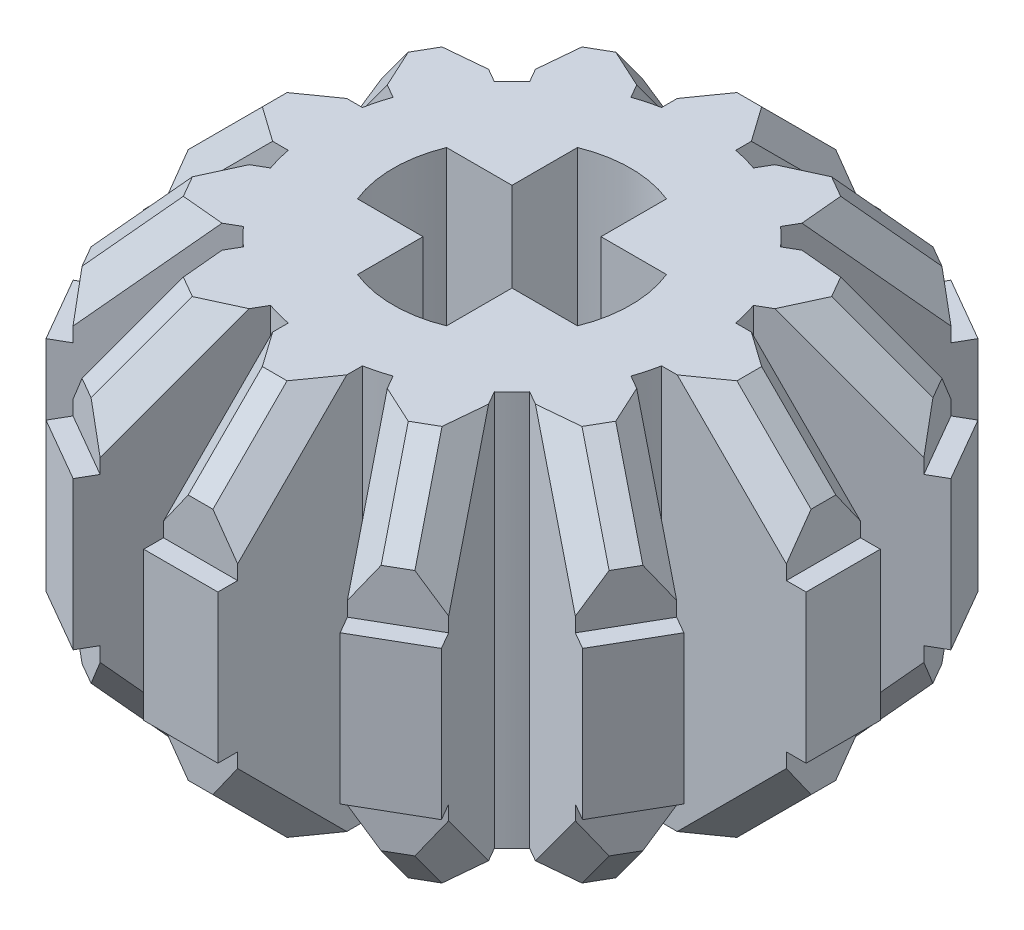
SolidWorks part; units mm, degrees
ref_plane "Front Plane" through (0, 0, 0) normal (0, 0, 1) x (1, 0, 0)
ref_plane "Top Plane" through (0, 0, 0) normal (0, 1, 0) x (1, 0, 0)
ref_plane "Right Plane" through (0, 0, 0) normal (1, 0, 0) x (0, 0, -1)
sketch "Sketch1" plane through (0, 0, 0) normal (0, 1, 0) x (1, 0, 0)
  circle A0 centre (0, 0) radius 3.85
  dimension "D1" = 7.7
extrude "Gear Body" add sketch "Sketch1" along normal mid plane 8
sketch "Sketch2" plane through (0, 0, 0) normal (0, 1, 0) x (1, 0, 0)
  line L1 (0.75, -6.7) -> (-0.75, -6.7)
  line L2 (0.75, -6.7) -> (0.75, 6.7)
  line L3 (0.75, 6.7) -> (-0.75, 6.7)
  line L4 (-0.75, -6.7) -> (-0.75, 6.7)
  line L5 (0.75, -6.7) -> (-0.75, 6.7) construction
  line L6 (0.75, 6.7) -> (-0.75, -6.7) construction
  circle A0 centre (0, 0) radius 3.85 construction
  circle A1 centre (0, 0) radius 3.85
  point P0 (0, 0)
  dimension "D1" = 1.5
  dimension "D2" = 13.4
extrude "Tooth Middle " add sketch "Sketch2" along normal mid plane 3 contours A1 L2 L3 L4
sketch "Sketch3" plane through (0, 0, 0) normal (0, 1, 0) x (1, 0, 0)
  line L0 (-0.75, 3.7762) -> (-0.75, 6.7) construction
  line L1 (0.75, -6.3) -> (-0.75, -6.3)
  line L2 (0.75, -6.3) -> (0.75, 6.3)
  line L3 (0.75, 6.3) -> (-0.75, 6.3)
  line L4 (-0.75, -6.3) -> (-0.75, 6.3)
  line L5 (0.75, -6.3) -> (-0.75, 6.3) construction
  line L6 (0.75, 6.3) -> (-0.75, -6.3) construction
  circle A0 centre (0, 0) radius 3.85 construction
  circle A1 centre (0, 0) radius 3.85
  point P0 (0, 0)
  dimension "D1" = 12.6
extrude "Tooth Outer" add sketch "Sketch3" along normal mid plane 8 contours A1 L2 L3 L4
chamfer "Chamfer1" distance 1.5 angle 45 2 edges at (0, -4, -6.3) (0, 4, -6.3)
chamfer "Chamfer2" distance 0.5 angle 45 4 edges at (0.75, -3.25, -5.55) (-0.75, -3.25, -5.55) (0.75, 3.25, -5.55) (-0.75, 3.25, -5.55)
pattern_circular "CirPattern1" count 12 over 360 about axis through (0, 0, 0) along (0, 1, 0) of "Tooth Middle ", "Tooth Outer", "Chamfer1", "Chamfer2"
sketch "Sketch4" plane through (0, 0, 0) normal (0, 1, 0) x (1, 0, 0)
  line L1 (2.4, -0.9) -> (-2.4, -0.9)
  line L2 (2.4, -0.9) -> (2.4, 0.9)
  line L3 (2.4, 0.9) -> (-2.4, 0.9)
  line L4 (-2.4, -0.9) -> (-2.4, 0.9)
  line L5 (2.4, -0.9) -> (-2.4, 0.9) construction
  line L6 (2.4, 0.9) -> (-2.4, -0.9) construction
  line L7 (0.9, -2.4) -> (-0.9, -2.4)
  line L8 (0.9, -2.4) -> (0.9, 2.4)
  line L9 (0.9, 2.4) -> (-0.9, 2.4)
  line L10 (-0.9, -2.4) -> (-0.9, 2.4)
  line L11 (0.9, -2.4) -> (-0.9, 2.4) construction
  line L12 (0.9, 2.4) -> (-0.9, -2.4) construction
  circle A0 centre (0, 0) radius 2.4
  dimension "D1" = 4.8
  dimension "D2" = 1.8
extrude "Axle Cut " cut sketch "Sketch4" against normal through all both and the other way through all contours L8 A0 L10 L3 | L3 A0 L1 L10 | A0 L8 L1 L10 | L1 A0 L3 L8 | L10 L1 L8 L3
